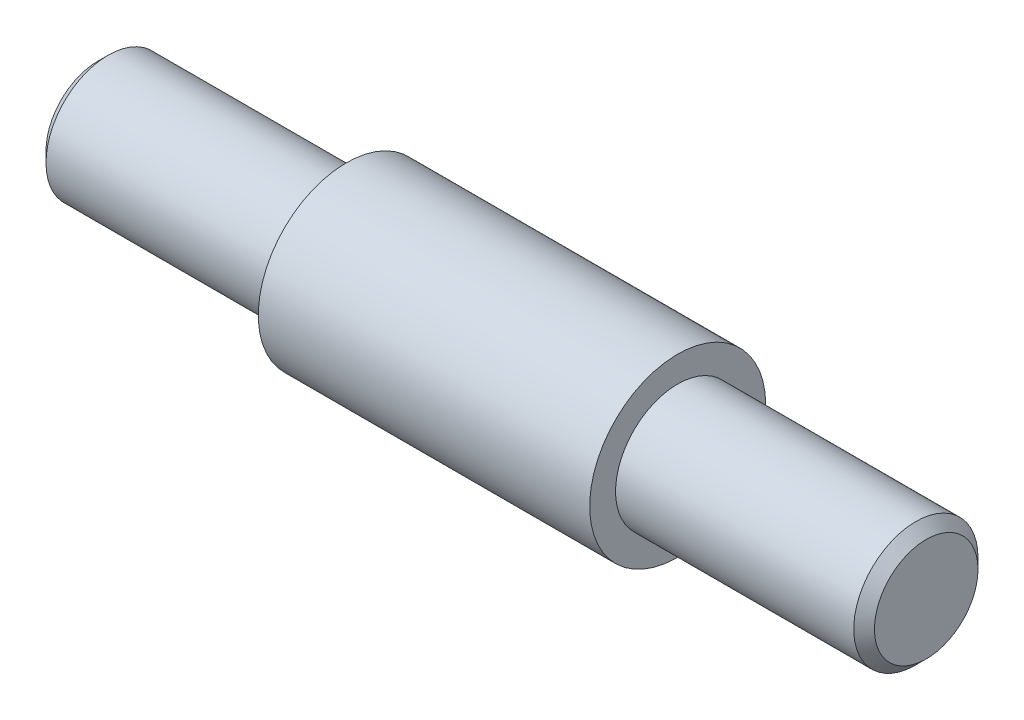
SolidWorks part; units mm, degrees
ref_plane "Front Plane" through (0, 0, 0) normal (0, 0, 1) x (1, 0, 0)
ref_plane "Top Plane" through (0, 0, 0) normal (0, 1, 0) x (1, 0, 0)
ref_plane "Right Plane" through (0, 0, 0) normal (1, 0, 0) x (0, 0, -1)
sketch "Sketch1" plane through (0, 0, 0) normal (0, 0, 1) x (1, 0, 0)
  line L0 (0, 0) -> (-20, 0)
  line L1 (0, 0) -> (20, 0)
  line L2 (20, 0) -> (20, 3)
  line L3 (20, 3) -> (8, 3)
  line L4 (8, 3) -> (8, 4.25)
  line L5 (8, 4.25) -> (-8, 4.25)
  line L6 (-8, 4.25) -> (-8, 3)
  line L7 (-8, 3) -> (-20, 3)
  line L8 (-20, 3) -> (-20, 0)
  dimension "D1" = 20
  dimension "D2" = 12
  dimension "D3" = 1.25
  dimension "D4" = 3
revolve "Revolve1" add sketch "Sketch1" angle 360 about L0
chamfer "Chamfer1" distance 0.5 angle 45 2 edges at (-20, 0, -3) (20, 0, -3)
